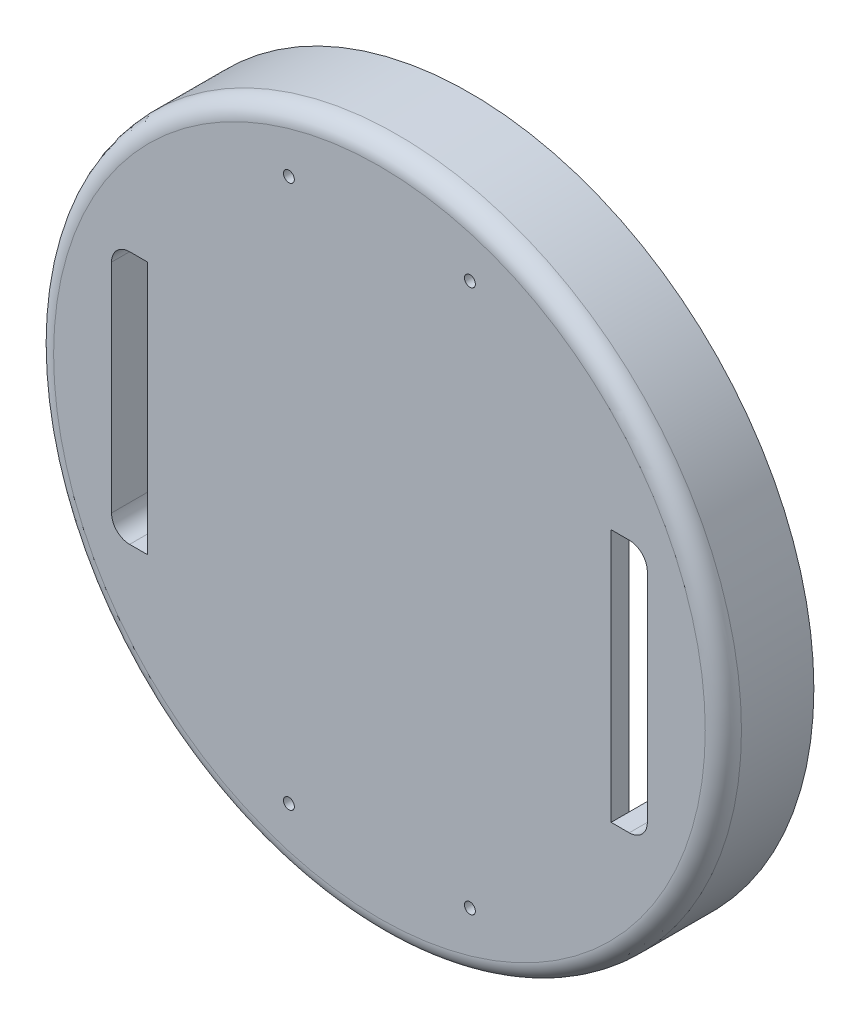
SolidWorks part; units mm, degrees
ref_plane "前基準面" through (0, 0, 0) normal (0, 0, 1) x (1, 0, 0)
ref_plane "上基準面" through (0, 0, 0) normal (0, 1, 0) x (1, 0, 0)
ref_plane "右基準面" through (0, 0, 0) normal (1, 0, 0) x (0, 0, -1)
sketch "草圖1" plane through (0, 0, 0) normal (0, 0, 1) x (1, 0, 0)
  line L0 (0, 132.1614) -> (0, -111.7346) construction
  line L1 (64, 64) -> (-64, 64)
  line L2 (64, 64) -> (64, 34.2103)
  line L3 (64, -64) -> (-64, -64)
  line L4 (-64, 64) -> (-64, 34.2103)
  line L5 (64, 64) -> (-64, -64) construction
  line L6 (64, -64) -> (-64, 64) construction
  line L7 (-182.3073, 0) -> (-74, 0) construction
  line L8 (-69, 0) -> (-69, -29.2103) construction
  line L9 (-69, 0) -> (64, 0) construction
  line L13 (-64, -34.2103) -> (-64, -64)
  line L16 (64, -34.2103) -> (64, -64)
  line L17 (64, 34.2103) -> (64, -34.2103)
  line L18 (-64, 34.2103) -> (-64, -34.2103)
  line L20 (74, 0) -> (189.0521, 0) construction
  circle A0 centre (0, 0) radius 95
  point P13 (-69, 0)
  point P31 (0, 0)
  dimension "D1" = 190
  dimension "D2" = 128
  dimension "D3" = 128
extrude "填料-伸長1" add sketch "草圖1" along normal blind 20 contours A0
sketch "草圖2" plane through (0, 0, 20) normal (0, 0, 1) x (1, 0, 0)
  circle A0 centre (0, 0) radius 95
extrude "填料-伸長2" add sketch "草圖2" along normal blind 5
fillet "圓角1" radius 5 1 edges at (95, 0, 25)
sketch "草圖5" plane through (0, 0, 0) normal (0, 0, -1) x (-1, 0, 0)
  line L0 (-119.1388, 0) -> (176.5975, 0) construction
  circle A0 centre (-25, 75) radius 1.5
  circle A1 centre (25, 75) radius 1.5
  circle A2 centre (25, -75) radius 1.5
  circle A3 centre (-25, -75) radius 1.5
  point P14 (0, 0)
  dimension "D1" = 3
  dimension "D2" = 3
  dimension "D3" = 75
  dimension "D4" = 75
  dimension "D5" = 25
  dimension "D6" = 50
  dimension "D7" = 2
extrude "除料-伸長2" cut sketch "草圖5" against normal through all
sketch "草圖6" plane through (0, 0, 20) normal (0, 0, -1) x (-1, 0, 0)
  line L0 (-64, 35) -> (-64, -35)
  line L1 (-64, -64) -> (-64, 64) construction
  line L2 (-64, -64) -> (-64, 64) construction
  line L3 (-64, -35) -> (-69, -35)
  line L4 (-64, 35) -> (-69, 35)
  line L5 (-74, 30) -> (-74, -30)
  line L6 (0, 103.0243) -> (0, -111.7516) construction
  line L7 (64, -35) -> (69, -35)
  line L8 (74, 30) -> (74, -30)
  line L9 (64, 35) -> (64, -35)
  line L10 (64, 35) -> (69, 35)
  arc A0 (-69, 35) -> (-74, 30) centre (-69, 30) ccw
  arc A1 (-69, -35) -> (-74, -30) centre (-69, -30) cw
  arc A2 (69, -35) -> (74, -30) centre (69, -30) ccw
  arc A3 (69, 35) -> (74, 30) centre (69, 30) cw
  dimension "D6" = 5
  dimension "D8" = 5
  dimension "D1" = 70
  dimension "D2" = 35
  dimension "D3" = 10
  dimension "D4" = 60
  dimension "D5" = 30
  dimension "D7" = 5
extrude "除料-伸長9" cut sketch "草圖6" against normal through all and the other way through all
